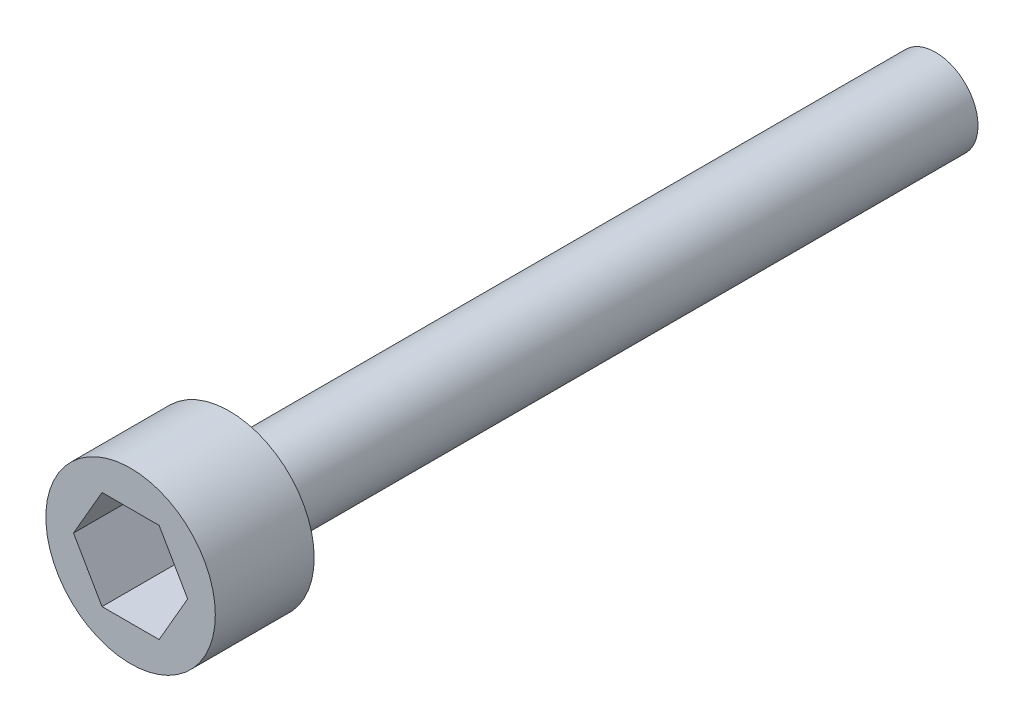
SolidWorks part; units mm, degrees
ref_plane "Front Plane" through (0, 0, 0) normal (0, 0, 1) x (1, 0, 0)
ref_plane "Top Plane" through (0, 0, 0) normal (0, 1, 0) x (1, 0, 0)
ref_plane "Right Plane" through (0, 0, 0) normal (1, 0, 0) x (0, 0, -1)
sketch "Sketch1" plane through (0, 0, 0) normal (0, 0, 1) x (1, 0, 0)
  circle A0 centre (0, 0) radius 3
  dimension "D1" = 6
extrude "Head Boss-Extrude1" add sketch "Sketch1" along normal blind 3.5
sketch "Sketch3" plane through (0, 0, 3.5) normal (0, 0, 1) x (1, 0, 0)
  line L0 (-1.0104, 1.75) -> (1.0104, 1.75)
  line L1 (1.0104, 1.75) -> (2.0207, 0)
  line L2 (2.0207, 0) -> (1.0104, -1.75)
  line L3 (1.0104, -1.75) -> (-1.0104, -1.75)
  line L4 (-1.0104, -1.75) -> (-2.0207, 0)
  line L5 (-2.0207, 0) -> (-1.0104, 1.75)
  line L6 (-2.0207, 0) -> (0, 0) construction
  line L7 (2.0207, 0) -> (0, 0) construction
  line L8 (-1.0104, -1.75) -> (0, 0) construction
  line L9 (0, 0) -> (1.0104, 1.75) construction
  line L10 (-1.0104, 1.75) -> (0, 0) construction
  line L11 (0, 0) -> (1.0104, -1.75) construction
  dimension "D1" = 60
  dimension "D2" = 60
  dimension "D3" = 60
  dimension "D4" = 60
  dimension "D5" = 60
  dimension "D6" = 3.5
extrude "Head Hex Cut-Extrude1" cut sketch "Sketch3" against normal blind 2.8
sketch "Sketch2" plane through (0, 0, 0) normal (0, 0, 1) x (1, 0, 0)
  circle A0 centre (0, 0) radius 1.5
  dimension "D1" = 3
extrude "Screw Boss-Extrude2" add sketch "Sketch2" against normal blind 25
